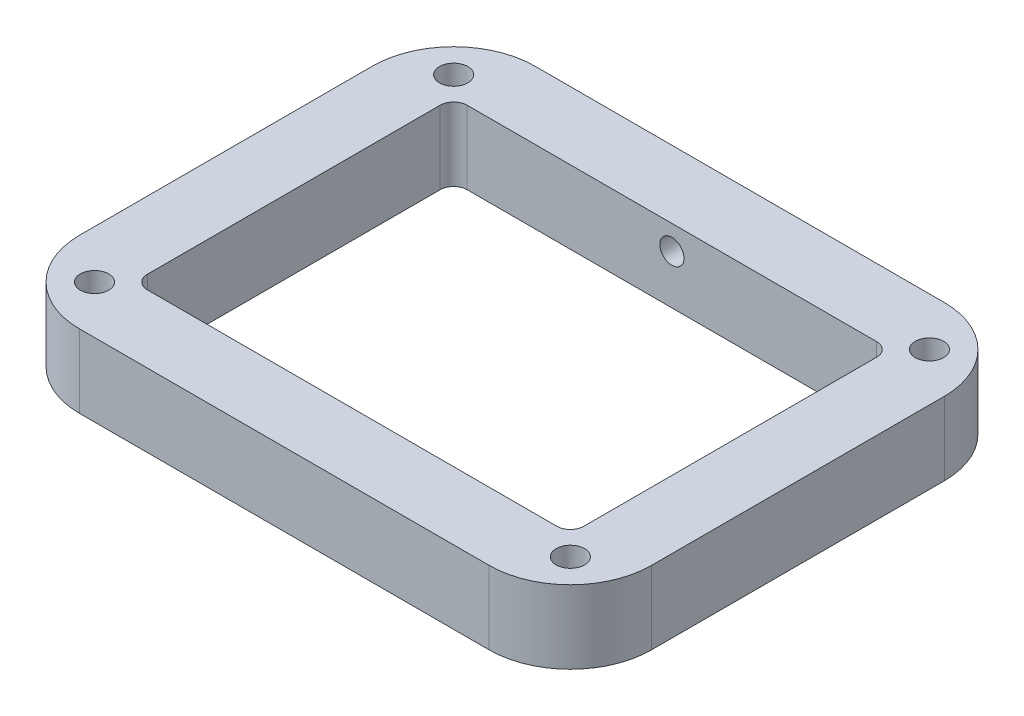
SolidWorks part; units mm, degrees
ref_plane "Front Plane" through (0, 0, 0) normal (0, 0, 1) x (1, 0, 0)
ref_plane "Top Plane" through (0, 0, 0) normal (0, 1, 0) x (1, 0, 0)
ref_plane "Right Plane" through (0, 0, 0) normal (1, 0, 0) x (0, 0, -1)
sketch "Sketch1" plane through (0, 0, 0) normal (0, 1, 0) x (1, 0, 0)
  line L0 (-47.5, -7.5125) -> (-47.5, -71.5125)
  line L1 (-44.75, -4.7625) -> (44.75, -4.7625)
  line L2 (47.5, -7.5125) -> (47.5, -71.5125)
  line L3 (-44.75, -74.2625) -> (44.75, -74.2625)
  line L4 (-44.75, 10.2375) -> (44.75, 10.2375)
  line L5 (62.5, -7.5125) -> (62.5, -71.5125)
  line L6 (-44.75, -89.2625) -> (44.75, -89.2625)
  line L7 (-62.5, -7.5125) -> (-62.5, -71.5125)
  arc A0 (-47.5, -71.5125) -> (-44.75, -74.2625) centre (-44.75, -71.5125) ccw construction
  arc A1 (44.75, -74.2625) -> (47.5, -71.5125) centre (44.75, -71.5125) ccw construction
  arc A2 (47.5, -7.5125) -> (44.75, -4.7625) centre (44.75, -7.5125) ccw construction
  arc A3 (-44.75, -4.7625) -> (-47.5, -7.5125) centre (-44.75, -7.5125) ccw construction
  arc A4 (-47.5, -71.5125) -> (-44.75, -74.2625) centre (-44.75, -71.5125) ccw
  arc A5 (44.75, -74.2625) -> (47.5, -71.5125) centre (44.75, -71.5125) ccw
  arc A6 (47.5, -7.5125) -> (44.75, -4.7625) centre (44.75, -7.5125) ccw
  arc A7 (-44.75, -4.7625) -> (-47.5, -7.5125) centre (-44.75, -7.5125) ccw
  arc A8 (62.5, -7.5125) -> (44.75, 10.2375) centre (44.75, -7.5125) ccw
  arc A9 (44.75, -89.2625) -> (62.5, -71.5125) centre (44.75, -71.5125) ccw
  arc A10 (-62.5, -71.5125) -> (-44.75, -89.2625) centre (-44.75, -71.5125) ccw
  arc A11 (-44.75, 10.2375) -> (-62.5, -7.5125) centre (-44.75, -7.5125) ccw
  dimension "D1" = 15
extrude "Boss-Extrude1" add sketch "Sketch1" along normal blind 16
sketch "Sketch2" plane through (0, 0, 4.7625) normal (0, 0, 1) x (1, 0, 0)
  circle A0 centre (0, 10.7219) radius 2.65
  dimension "D1" = 5.3
extrude "Cut-Extrude1" cut sketch "Sketch2" against normal blind 20
sketch "Sketch3" plane through (0, 0, 0) normal (0, 1, 0) x (1, 0, 0)
  line L0 (44.75, -4.7625) -> (-44.75, -4.7625) construction
  line L1 (-44.75, -74.2625) -> (44.75, -74.2625) construction
  line L2 (47.5, -71.5125) -> (47.5, -7.5125) construction
  line L3 (-47.5, -7.5125) -> (-47.5, -71.5125) construction
  line L4 (-44.75, -74.2625) -> (44.75, -74.2625)
  line L5 (47.5, -71.5125) -> (47.5, -7.5125)
  line L6 (-47.5, -7.5125) -> (-47.5, -71.5125)
  line L7 (44.75, -4.7625) -> (-44.75, -4.7625)
  line L12 (-47.7, -7.5125) -> (-47.7, -71.5125)
  line L13 (-44.75, -74.4625) -> (44.75, -74.4625)
  line L14 (47.7, -71.5125) -> (47.7, -7.5125)
  line L15 (44.75, -4.5625) -> (-44.75, -4.5625)
  arc A0 (-47.5, -71.5125) -> (-44.75, -74.2625) centre (-44.75, -71.5125) ccw construction
  arc A1 (44.75, -74.2625) -> (47.5, -71.5125) centre (44.75, -71.5125) ccw construction
  arc A2 (47.5, -7.5125) -> (44.75, -4.7625) centre (44.75, -7.5125) ccw construction
  arc A3 (-44.75, -4.7625) -> (-47.5, -7.5125) centre (-44.75, -7.5125) ccw construction
  arc A4 (-47.5, -71.5125) -> (-44.75, -74.2625) centre (-44.75, -71.5125) ccw
  arc A5 (44.75, -74.2625) -> (47.5, -71.5125) centre (44.75, -71.5125) ccw
  arc A6 (47.5, -7.5125) -> (44.75, -4.7625) centre (44.75, -7.5125) ccw
  arc A7 (-44.75, -4.7625) -> (-47.5, -7.5125) centre (-44.75, -7.5125) ccw
  arc A12 (-44.75, -4.5625) -> (-47.7, -7.5125) centre (-44.75, -7.5125) ccw
  arc A13 (-47.7, -71.5125) -> (-44.75, -74.4625) centre (-44.75, -71.5125) ccw
  arc A14 (44.75, -74.4625) -> (47.7, -71.5125) centre (44.75, -71.5125) ccw
  arc A15 (47.7, -7.5125) -> (44.75, -4.5625) centre (44.75, -7.5125) ccw
  dimension "D1" = 0.2
extrude "Cut-Extrude2" cut sketch "Sketch3" against normal through all both and the other way through all
sketch "Sketch4" plane through (0, 0, 0) normal (0, -1, 0) x (1, 0, 0)
  line L22 (-55, 71.5125) -> (-55, 7.5125)
  line L23 (-44.75, -2.7375) -> (44.75, -2.7375)
  line L24 (55, 7.5125) -> (55, 71.5125)
  line L25 (44.75, 81.7625) -> (-44.75, 81.7625)
  line L26 (-55, 71.5125) -> (-55, 7.5125) construction
  line L27 (-44.75, -2.7375) -> (44.75, -2.7375) construction
  line L28 (55, 7.5125) -> (55, 71.5125) construction
  line L29 (44.75, 81.7625) -> (-44.75, 81.7625) construction
  circle A28 centre (-51.9978, 78.7603) radius 3.1
  circle A29 centre (51.9978, 78.7603) radius 3.1
  circle A30 centre (51.9978, 0.2647) radius 3.1
  circle A31 centre (-51.9978, 0.2647) radius 3.1
  arc A32 (-55, 7.5125) -> (-44.75, -2.7375) centre (-44.75, 7.5125) ccw
  arc A33 (44.75, -2.7375) -> (55, 7.5125) centre (44.75, 7.5125) ccw
  arc A34 (55, 71.5125) -> (44.75, 81.7625) centre (44.75, 71.5125) ccw
  arc A35 (-44.75, 81.7625) -> (-55, 71.5125) centre (-44.75, 71.5125) ccw
  arc A36 (-55, 7.5125) -> (-44.75, -2.7375) centre (-44.75, 7.5125) ccw construction
  arc A37 (44.75, -2.7375) -> (55, 7.5125) centre (44.75, 7.5125) ccw construction
  arc A38 (55, 71.5125) -> (44.75, 81.7625) centre (44.75, 71.5125) ccw construction
  arc A39 (-44.75, 81.7625) -> (-55, 71.5125) centre (-44.75, 71.5125) ccw construction
  dimension "D2" = 6.2
  dimension "D1" = 7.5
extrude "Cut-Extrude3" cut sketch "Sketch4" against normal through all both and the other way through all
sketch "Sketch5" plane through (0, 0, 0) normal (0, -1, 0) x (1, 0, 0)
  line L1 (-46.1089, 78.7603) -> (-49.0534, 83.8603)
  line L2 (-49.0534, 83.8603) -> (-54.9423, 83.8603)
  line L3 (-54.9423, 83.8603) -> (-57.8868, 78.7603)
  line L4 (-57.8868, 78.7603) -> (-54.9423, 73.6603)
  line L5 (-54.9423, 73.6603) -> (-49.0534, 73.6603)
  line L6 (-49.0534, 73.6603) -> (-46.1089, 78.7603)
  line L7 (57.8868, 78.7603) -> (54.9423, 83.8603)
  line L8 (54.9423, 83.8603) -> (49.0534, 83.8603)
  line L9 (49.0534, 83.8603) -> (46.1089, 78.7603)
  line L10 (46.1089, 78.7603) -> (49.0534, 73.6603)
  line L11 (49.0534, 73.6603) -> (54.9423, 73.6603)
  line L12 (54.9423, 73.6603) -> (57.8868, 78.7603)
  line L13 (57.8868, 0.2647) -> (54.9423, 5.3647)
  line L14 (54.9423, 5.3647) -> (49.0534, 5.3647)
  line L15 (49.0534, 5.3647) -> (46.1089, 0.2647)
  line L16 (46.1089, 0.2647) -> (49.0534, -4.8353)
  line L17 (49.0534, -4.8353) -> (54.9423, -4.8353)
  line L18 (54.9423, -4.8353) -> (57.8868, 0.2647)
  line L19 (-46.1089, 0.2647) -> (-49.0534, 5.3647)
  line L20 (-49.0534, 5.3647) -> (-54.9423, 5.3647)
  line L21 (-54.9423, 5.3647) -> (-57.8868, 0.2647)
  line L22 (-57.8868, 0.2647) -> (-54.9423, -4.8353)
  line L23 (-54.9423, -4.8353) -> (-49.0534, -4.8353)
  line L24 (-49.0534, -4.8353) -> (-46.1089, 0.2647)
  circle A0 centre (-51.9978, 78.7603) radius 5.1 construction
  circle A1 centre (51.9978, 78.7603) radius 5.1 construction
  circle A2 centre (51.9978, 0.2647) radius 5.1 construction
  circle A3 centre (-51.9978, 0.2647) radius 5.1 construction
  dimension "D1" = 10.2
extrude "Cut-Extrude4" cut sketch "Sketch5" against normal blind 6 and the other way through all
